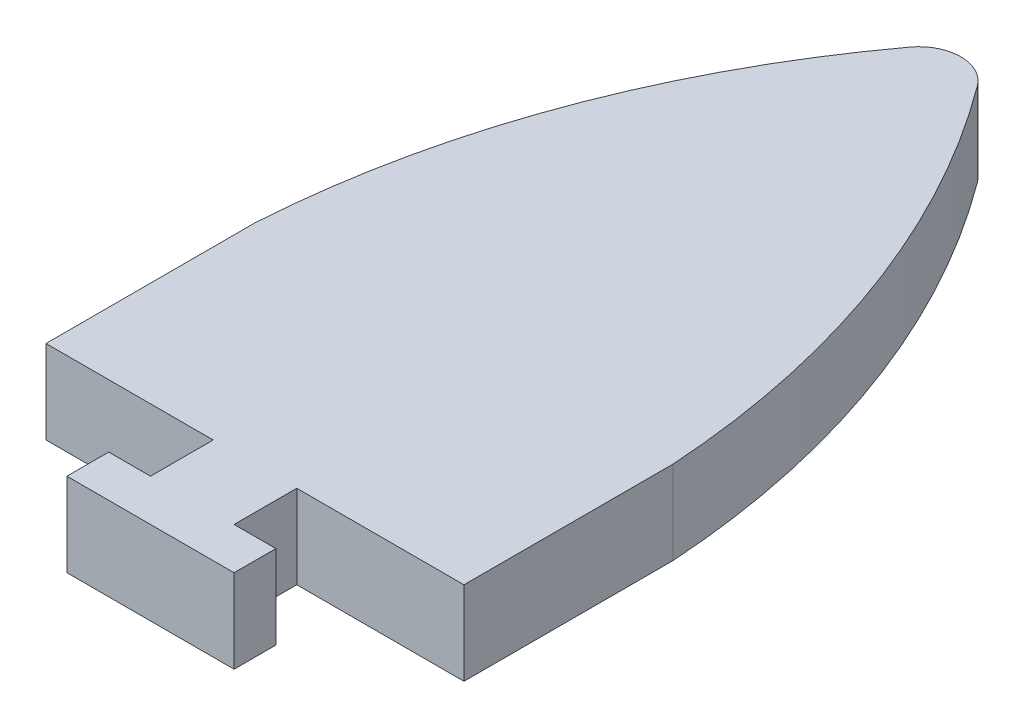
SolidWorks part; units mm, degrees
ref_plane "Спереди" through (0, 0, 0) normal (0, 0, 1) x (1, 0, 0)
ref_plane "Сверху" through (0, 0, 0) normal (0, 1, 0) x (1, 0, 0)
ref_plane "Справа" through (0, 0, 0) normal (1, 0, 0) x (0, 0, -1)
sketch "Эскиз1" plane through (0, 0, 0) normal (0, 1, 0) x (1, 0, 0)
  line L0 (0, 0) -> (0, -22.5) construction
  line L1 (10, -17.5) -> (2, -17.5)
  line L2 (10, -17.5) -> (10, -7.5)
  line L4 (-10, -17.5) -> (-10, -7.5)
  line L5 (-4, -22.5) -> (4, -22.5)
  line L6 (4, -22.5) -> (4, -20.5)
  line L7 (4, -20.5) -> (2, -20.5)
  line L8 (2, -20.5) -> (2, -17.5)
  line L9 (-4, -22.5) -> (-4, -20.5)
  line L10 (-4, -20.5) -> (-2, -20.5)
  line L11 (-2, -20.5) -> (-2, -17.5)
  line L12 (-2, -17.5) -> (-10, -17.5)
  arc A0 (-1.6075, 15.4595) -> (-10, -7.5) centre (33.1259, -10.2503) ccw
  arc A1 (1.6075, 15.4595) -> (10, -7.5) centre (-33.1259, -10.2503) cw
  arc A2 (1.6075, 15.4595) -> (-1.6075, 15.4595) centre (0, 14.2696) ccw
  point P0 (0, 0)
  point P6 (-10, -7.5)
  point P14 (0, 17.5)
  dimension "D1" = 2
  dimension "D2" = 20
  dimension "D3" = 10
  dimension "D5" = 4
  dimension "D6" = 2
  dimension "D7" = 2
extrude "Бобышка-Вытянуть1" add sketch "Эскиз1" along normal blind 4
